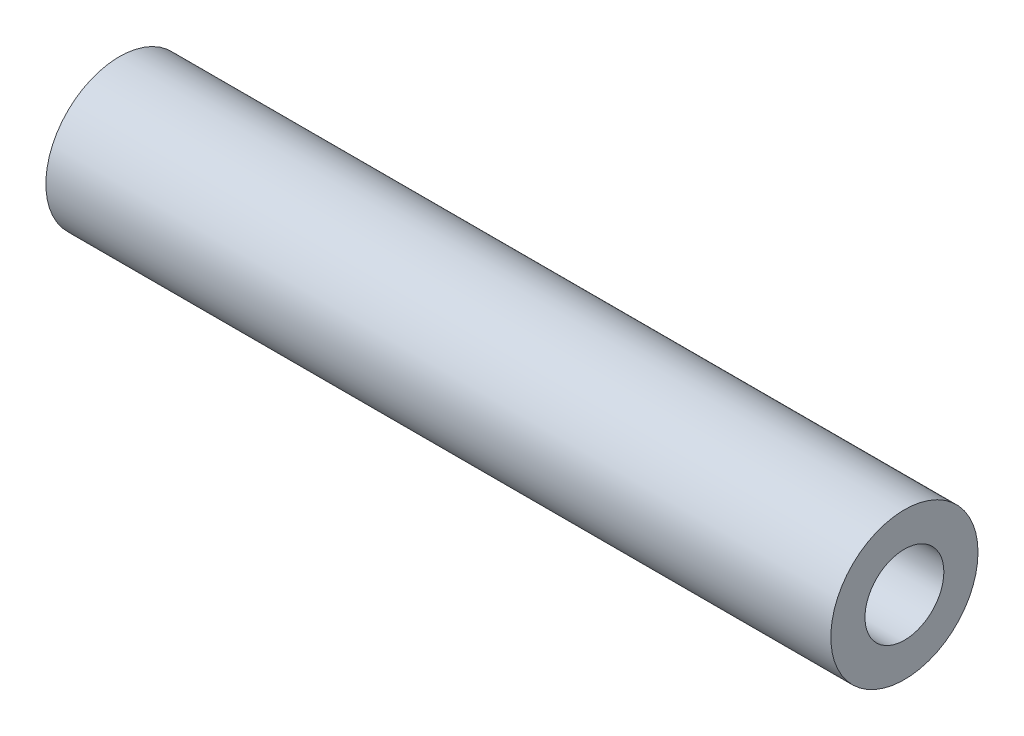
SolidWorks part; units mm, degrees
ref_plane "Front" through (0, 0, 0) normal (0, 0, 1) x (1, 0, 0)
ref_plane "Top" through (0, 0, 0) normal (0, 1, 0) x (1, 0, 0)
ref_plane "Right" through (0, 0, 0) normal (1, 0, 0) x (0, 0, -1)
sketch "Sketch1" plane through (0, 0, 0) normal (1, 0, 0) x (0, 0, -1)
  circle A0 centre (0, 0) radius 2.5527
  circle A1 centre (0, 0) radius 4.7625
  dimension "D1" = 9.525
  dimension "D2" = 5.1054
extrude "Boss-Extrude1" add sketch "Sketch1" along normal blind 50.8 contours A1
